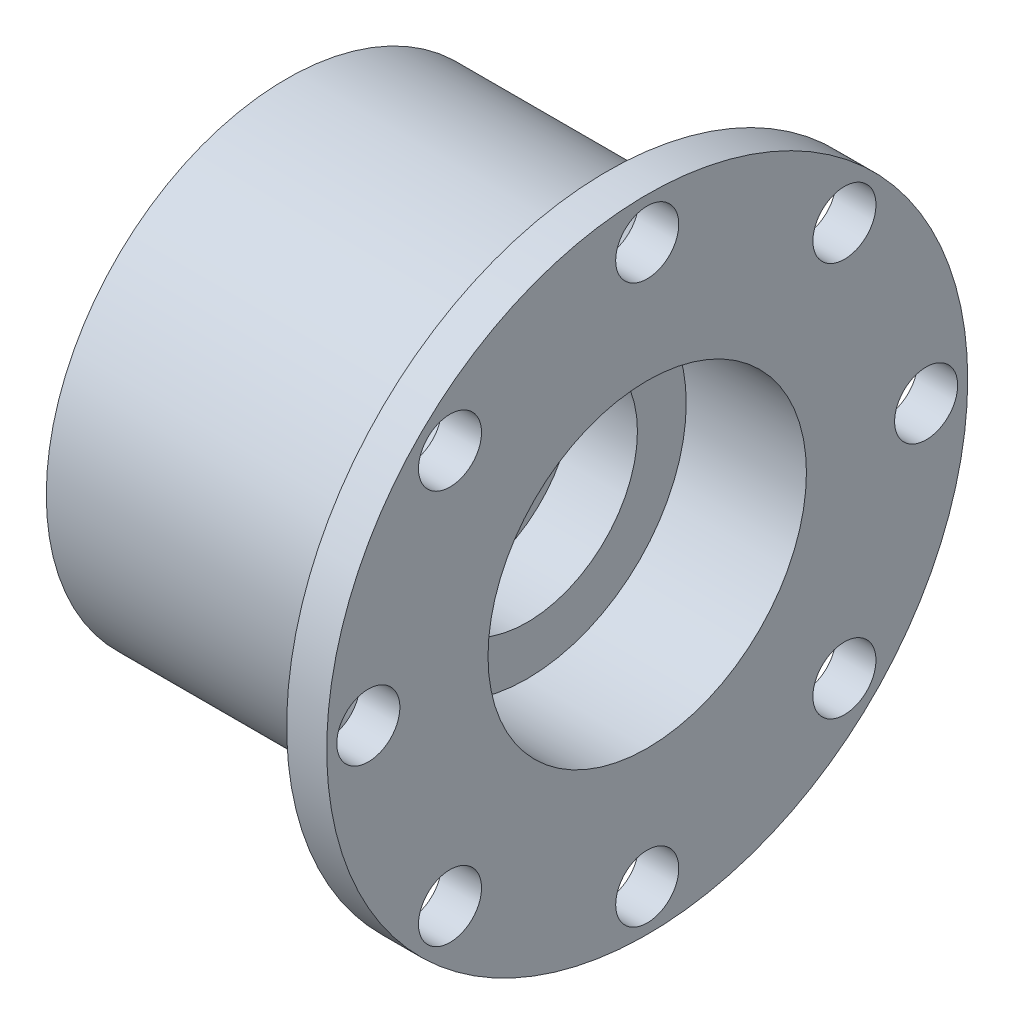
SolidWorks part; units mm, degrees
ref_plane "Front Plane" through (0, 0, 0) normal (0, 0, 1) x (1, 0, 0)
ref_plane "Top Plane" through (0, 0, 0) normal (0, 1, 0) x (1, 0, 0)
ref_plane "Right Plane" through (0, 0, 0) normal (1, 0, 0) x (0, 0, -1)
sketch "Sketch1" plane through (0, 0, 0) normal (1, 0, 0) x (0, 0, -1)
  circle A0 centre (0, 0) radius 38.1
  dimension "D1" = 76.2
extrude "Boss-Extrude1" add sketch "Sketch1" along normal blind 38.1
sketch "Sketch2" plane through (38.1, 0, 0) normal (1, 0, 0) x (0, 0, -1)
  circle A0 centre (0, 0) radius 17.5
  dimension "D1" = 35
extrude "Cut-Extrude1" cut sketch "Sketch2" against normal blind 10.25
sketch "Sketch3" plane through (27.85, 0, 0) normal (1, 0, 0) x (0, 0, -1)
  point P0 (0, 0)
hole_wizard "Ø25.0mm Dowel Hole1" positions "Sketch3" profile "Sketch5" hole size "Ø25.0" standard "ANSI Metric" end condition through all
sketch "Sketch5" plane through (27.85, 0, 0) normal (0, 1, 0) x (0, 0, -1)
  line L0 (0, 0) -> (0, 27.85)
  line L1 (0, 27.85) -> (8.5, 27.85)
  line L2 (8.5, 27.85) -> (8.5, 0)
  line L5 (8.5, 0) -> (0, 0)
  line L11 (0, -6.35) -> (0, 107.95) construction
  dimension "Thru Hole Dia." = 17
  dimension "Thru Hole Depth" = 27.85
sketch "Sketch14" plane through (38.1, 0, 0) normal (1, 0, 0) x (0, 0, -1)
  circle A0 centre (0, 0) radius 25.2353
  circle A1 centre (0, 0) radius 38.1 construction
  circle A2 centre (0, 0) radius 38.1
extrude "Boss-Extrude3" add sketch "Sketch14" along normal blind 19.05
sketch "Sketch7" plane through (57.15, 0, 0) normal (1, 0, 0) x (0, 0, -1)
  circle A0 centre (0, 0) radius 50.8
  circle A3 centre (0, 0) radius 25.2353 construction
  circle A4 centre (0, 0) radius 25.2353
  dimension "D1" = 101.6
extrude "Boss-Extrude2" add sketch "Sketch7" against normal blind 6.35
sketch "Sketch8" plane through (0, 0, 0) normal (-1, 0, 0) x (0, 0, 1)
  circle A0 centre (0, 0) radius 20
  dimension "D1" = 40
extrude "Cut-Extrude2" cut sketch "Sketch8" against normal blind 13
sketch "Sketch12" plane through (50.8, 0, 0) normal (-1, 0, 0) x (0, 0, 1)
  point P0 (-44.2067, 0)
  point P4 (-31.2588, 31.2588)
  point P5 (0, 44.2067)
  point P6 (31.2588, 31.2588)
  point P7 (44.2067, 0)
  point P8 (31.2588, -31.2588)
  point P9 (0, -44.2067)
  point P10 (-31.2588, -31.2588)
  point P11 (0, 0)
  dimension "D1" = 8
hole_wizard "M8 Clearance Hole1" positions "Sketch12" profile "Sketch13" hole size "M8" standard "ANSI Metric" end condition through all
sketch "Sketch13" plane through (50.8, 0, -44.2067) normal (0, 1, 0) x (0, 0, 1)
  line L0 (0, 0) -> (0, 6.35)
  line L1 (0, 6.35) -> (5, 6.35)
  line L2 (5, 6.35) -> (5, 0)
  line L5 (5, 0) -> (0, 0)
  line L11 (0, -6.35) -> (0, 107.95) construction
  dimension "Thru Hole Dia." = 10
  dimension "Thru Hole Depth" = 6.35
